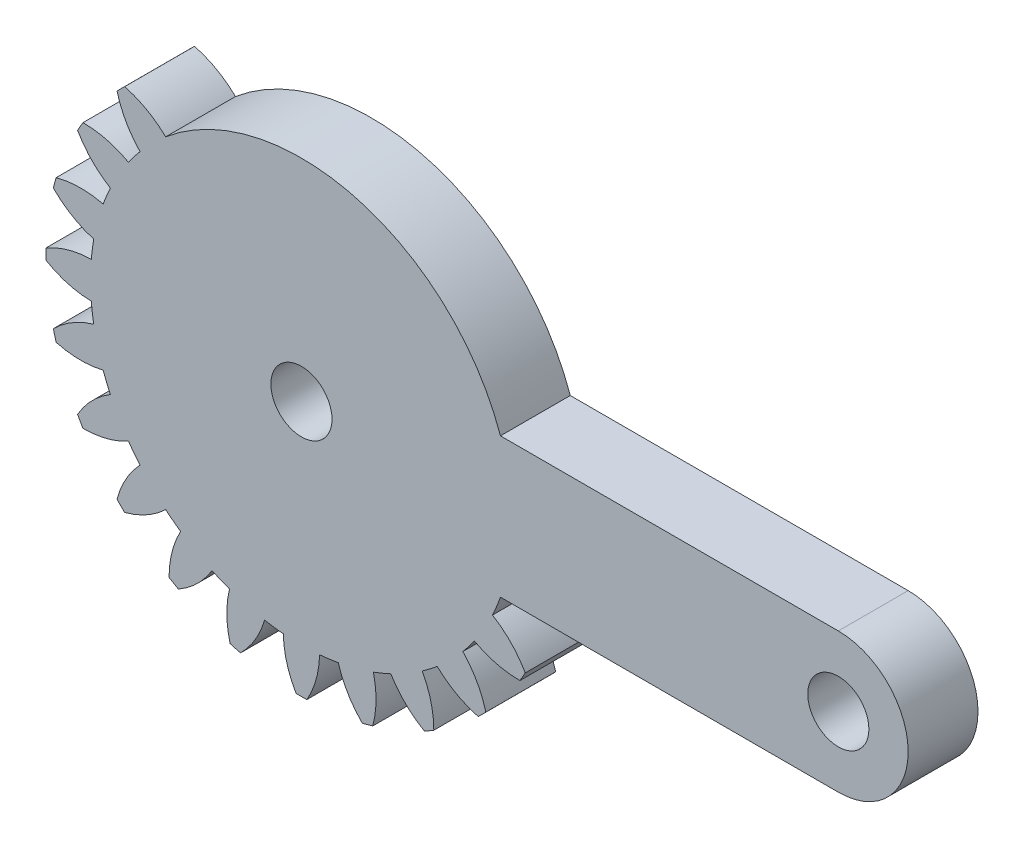
SolidWorks part; units mm, degrees
ref_plane "Front Plane" through (0, 0, 0) normal (0, 0, 1) x (1, 0, 0)
ref_plane "Top Plane" through (0, 0, 0) normal (0, 1, 0) x (1, 0, 0)
ref_plane "Right Plane" through (0, 0, 0) normal (1, 0, 0) x (0, 0, -1)
sketch "Sketch1" plane through (0, 0, 0) normal (0, 0, 1) x (1, 0, 0)
  line L0 (0, 0) -> (0, 14.63) construction
  line L1 (0, 0) -> (30.75, 0) construction
  line L2 (11.3985, 4) -> (30.75, 4)
  line L4 (30.75, -4) -> (11.3985, -4)
  circle A0 centre (0, 0) radius 1.75
  circle A1 centre (0, 0) radius 12.08
  circle A2 centre (0, 0) radius 14.63
  arc A3 (0.31, 14.6267) -> (1.04, 12.0351) centre (-4.3586, 11.913) cw
  arc A4 (-0.31, 14.6267) -> (-1.04, 12.0351) centre (4.3586, 11.913) ccw
  arc A5 (4.0851, 14.0481) -> (4.1195, 11.3559) centre (-1.1268, 12.6352) cw
  arc A6 (3.4862, 14.2086) -> (2.1104, 11.8942) centre (7.2934, 10.379) ccw
  arc A7 (7.5818, 12.5121) -> (6.9182, 9.9027) centre (2.1818, 12.4963) cw
  arc A8 (7.0449, 12.8221) -> (5.1169, 10.9427) centre (9.7312, 8.1377) ccw
  arc A9 (10.5619, 10.1234) -> (9.2455, 7.7747) centre (5.3418, 11.5058) cw
  arc A10 (10.1234, 10.5619) -> (7.7747, 9.2455) centre (11.5058, 5.3418) ccw
  arc A11 (12.8221, 7.0449) -> (10.9427, 5.1169) centre (8.1377, 9.7312) cw
  arc A12 (12.5121, 7.5818) -> (9.9027, 6.9182) centre (12.4963, 2.1818) ccw
  arc A13 (14.2086, 3.4862) -> (11.8942, 2.1104) centre (10.379, 7.2934) cw
  arc A14 (14.0481, 4.0851) -> (11.3559, 4.1195) centre (12.6352, -1.1268) ccw
  arc A15 (14.6267, -0.31) -> (12.0351, -1.04) centre (11.913, 4.3586) cw
  arc A16 (14.6267, 0.31) -> (12.0351, 1.04) centre (11.913, -4.3586) ccw
  arc A17 (14.0481, -4.0851) -> (11.3559, -4.1195) centre (12.6352, 1.1268) cw
  arc A18 (14.2086, -3.4862) -> (11.8942, -2.1104) centre (10.379, -7.2934) ccw
  arc A19 (12.5121, -7.5818) -> (9.9027, -6.9182) centre (12.4963, -2.1818) cw
  arc A20 (12.8221, -7.0449) -> (10.9427, -5.1169) centre (8.1377, -9.7312) ccw
  arc A21 (10.1234, -10.5619) -> (7.7747, -9.2455) centre (11.5058, -5.3418) cw
  arc A22 (10.5619, -10.1234) -> (9.2455, -7.7747) centre (5.3418, -11.5058) ccw
  arc A23 (7.0449, -12.8221) -> (5.1169, -10.9427) centre (9.7312, -8.1377) cw
  arc A24 (7.5818, -12.5121) -> (6.9182, -9.9027) centre (2.1818, -12.4963) ccw
  arc A25 (3.4862, -14.2086) -> (2.1104, -11.8942) centre (7.2934, -10.379) cw
  arc A26 (4.0851, -14.0481) -> (4.1195, -11.3559) centre (-1.1268, -12.6352) ccw
  arc A27 (-0.31, -14.6267) -> (-1.04, -12.0351) centre (4.3586, -11.913) cw
  arc A28 (0.31, -14.6267) -> (1.04, -12.0351) centre (-4.3586, -11.913) ccw
  arc A29 (-4.0851, -14.0481) -> (-4.1195, -11.3559) centre (1.1268, -12.6352) cw
  arc A30 (-3.4862, -14.2086) -> (-2.1104, -11.8942) centre (-7.2934, -10.379) ccw
  arc A31 (-7.5818, -12.5121) -> (-6.9182, -9.9027) centre (-2.1818, -12.4963) cw
  arc A32 (-7.0449, -12.8221) -> (-5.1169, -10.9427) centre (-9.7312, -8.1377) ccw
  arc A33 (-10.5619, -10.1234) -> (-9.2455, -7.7747) centre (-5.3418, -11.5058) cw
  arc A34 (-10.1234, -10.5619) -> (-7.7747, -9.2455) centre (-11.5058, -5.3418) ccw
  arc A35 (-12.8221, -7.0449) -> (-10.9427, -5.1169) centre (-8.1377, -9.7312) cw
  arc A36 (-12.5121, -7.5818) -> (-9.9027, -6.9182) centre (-12.4963, -2.1818) ccw
  arc A37 (-14.2086, -3.4862) -> (-11.8942, -2.1104) centre (-10.379, -7.2934) cw
  arc A38 (-14.0481, -4.0851) -> (-11.3559, -4.1195) centre (-12.6352, 1.1268) ccw
  arc A39 (-14.6267, 0.31) -> (-12.0351, 1.04) centre (-11.913, -4.3586) cw
  arc A40 (-14.6267, -0.31) -> (-12.0351, -1.04) centre (-11.913, 4.3586) ccw
  arc A41 (-14.0481, 4.0851) -> (-11.3559, 4.1195) centre (-12.6352, -1.1268) cw
  arc A42 (-14.2086, 3.4862) -> (-11.8942, 2.1104) centre (-10.379, 7.2934) ccw
  arc A43 (-12.5121, 7.5818) -> (-9.9027, 6.9182) centre (-12.4963, 2.1818) cw
  arc A44 (-12.8221, 7.0449) -> (-10.9427, 5.1169) centre (-8.1377, 9.7312) ccw
  arc A45 (-10.1234, 10.5619) -> (-7.7747, 9.2455) centre (-11.5058, 5.3418) cw
  arc A46 (-10.5619, 10.1234) -> (-9.2455, 7.7747) centre (-5.3418, 11.5058) ccw
  arc A47 (-7.0449, 12.8221) -> (-5.1169, 10.9427) centre (-9.7312, 8.1377) cw
  arc A48 (-7.5818, 12.5121) -> (-6.9182, 9.9027) centre (-2.1818, 12.4963) ccw
  arc A49 (-3.4862, 14.2086) -> (-2.1104, 11.8942) centre (-7.2934, 10.379) cw
  arc A50 (-4.0851, 14.0481) -> (-4.1195, 11.3559) centre (1.1268, 12.6352) ccw
  arc A51 (30.75, 4) -> (30.75, -4) centre (30.75, 0) cw
  circle A52 centre (30.75, 0) radius 1.75
  arc A53 (-11.8942, 2.1104) -> (-11.3559, 4.1195) centre (0, 0) cw
  arc A54 (-14.2086, 3.4862) -> (-14.0481, 4.0851) centre (0, 0) cw
  point P153 (0, 0)
  dimension "D1" = 3.5
  dimension "D2" = 24.16
  dimension "D3" = 29.26
  dimension "D6" = 5.4
  dimension "D9" = 4
  dimension "D10" = 3.5
  dimension "D4" = 0.62
  dimension "D5" = 2.08
  dimension "D8" = 30.75
  dimension "D11" = 1.0796
  dimension "D7" = 24
extrude "Boss-Extrude3" add sketch "Sketch1" along normal blind 4 contours A16 A2 A13 A1 | A2 A16 A1 A15 | A18 A2 A15 A1 | A2 A18 A1 L4 | A2 A20 A1 A19 | A2 A22 A1 A21 | A2 A24 A1 A23 | A1 | A2 A26 A1 A25 | A2 A28 A1 A27 | A2 A30 A1 A29 | A2 A32 A1 A31 | A2 A34 A1 A33 | A2 A36 A1 A35 | A2 A38 A1 A37 | A2 A40 A1 A39 | A2 A42 A1 A41 | A2 A44 A1 A43 | A2 A46 A1 A45 | A13 A2 L2 A1 | A51 L2 A2 L4 A52
sketch "Sketch3" plane through (0, 0, 4) normal (0, 0, 1) x (1, 0, 0)
  line L0 (-4.5, 0) -> (4.5, 0) construction
